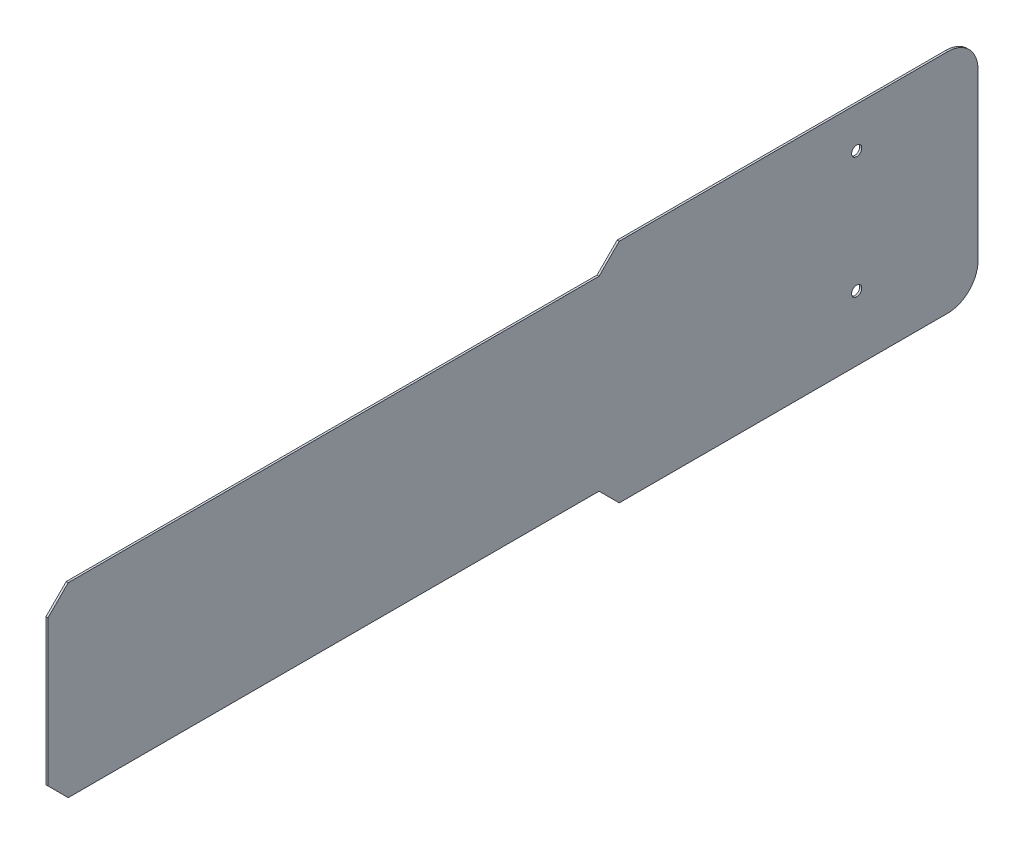
SolidWorks part; units mm, degrees
ref_plane "Front Plane" through (0, 0, 0) normal (0, 0, 1) x (1, 0, 0)
ref_plane "Top Plane" through (0, 0, 0) normal (0, 1, 0) x (1, 0, 0)
ref_plane "Right Plane" through (0, 0, 0) normal (1, 0, 0) x (0, 0, -1)
sketch "Sketch2" plane through (0, 0, 0) normal (-1, 0, 0) x (0, 1, 0)
  line L1 (-55.0231, 28.6615) -> (-32.6031, 28.6615)
  line L2 (-55.0231, 28.6615) -> (-55.0231, -63.3385)
  line L3 (-55.0231, -63.3385) -> (-32.6031, -63.3385)
  line L4 (-32.6031, 28.6615) -> (-32.6031, -63.3385)
  dimension "D1" = 92
  dimension "D2" = 22.42
extrude "Boss-Extrude2" add sketch "Sketch2" along normal blind 0.2 contours L2 L3 L4 L1
fillet "Fillet4" radius 3 1 edges at (-0.1, -55.0231, -28.6615)
fillet "Fillet7" radius 3 1 edges at (-0.1, -32.6031, -28.6615)
sketch "Sketch4" plane through (-0.2, 0, 0) normal (-1, 0, 0) x (0, 1, 0)
  line L0 (-55.0231, 25.6615) -> (-55.0231, -63.3385) construction
  line L1 (-55.0231, -8.8285) -> (-53.0231, -8.8285)
  line L2 (-55.0231, -8.8285) -> (-55.0231, -63.3385)
  line L3 (-55.0231, -63.3385) -> (-53.0231, -63.3385)
  line L4 (-53.0231, -8.8285) -> (-53.0231, -63.3385)
  line L5 (-55.0231, -63.3385) -> (-32.6031, -63.3385) construction
  dimension "D1" = 2
  dimension "D2" = 54.51
extrude "Cut-Extrude1" cut sketch "Sketch4" against normal blind 0.2
sketch "Sketch5" plane through (-0.2, 0, 0) normal (-1, 0, 0) x (0, 1, 0)
  line L1 (-34.6031, -8.8285) -> (-32.6031, -8.8285)
  line L2 (-34.6031, -8.8285) -> (-34.6031, -63.3385)
  line L3 (-34.6031, -63.3385) -> (-32.6031, -63.3385)
  line L4 (-32.6031, -8.8285) -> (-32.6031, -63.3385)
  dimension "D1" = 2
  dimension "D2" = 54.51
extrude "Cut-Extrude2" cut sketch "Sketch5" against normal blind 0.2
sketch "Sketch6" plane through (-0.2, 0, 0) normal (-1, 0, 0) x (0, 1, 0)
  line L0 (-53.0231, -63.3385) -> (-53.0231, -61.3385)
  line L1 (-53.0231, -63.3385) -> (-53.0231, -8.8285) construction
  line L2 (-53.0231, -63.3385) -> (-51.0231, -63.3385)
  line L3 (-53.0231, -63.3385) -> (-34.6031, -63.3385) construction
  line L4 (-53.0231, -61.3385) -> (-51.0231, -63.3385)
extrude "Cut-Extrude3" cut sketch "Sketch6" against normal blind 0.2
sketch "Sketch7" plane through (-0.2, 0, 0) normal (-1, 0, 0) x (0, 1, 0)
  line L0 (-34.6031, -63.3385) -> (-34.6031, -61.3385)
  line L1 (-34.6031, -8.8285) -> (-34.6031, -63.3385) construction
  line L2 (-34.6031, -63.3385) -> (-36.6031, -63.3385)
  line L3 (-51.0231, -63.3385) -> (-34.6031, -63.3385) construction
  line L4 (-34.6031, -61.3385) -> (-36.6031, -63.3385)
extrude "Cut-Extrude4" cut sketch "Sketch7" against normal blind 0.2
sketch "Sketch8" plane through (-0.2, 0, 0) normal (-1, 0, 0) x (0, 1, 0)
  line L0 (-53.0231, -8.8285) -> (-55.0231, -8.8285)
  line L2 (-55.0231, -8.8285) -> (-55.0231, -6.8285)
  line L3 (-55.0231, 25.6615) -> (-55.0231, -8.8285) construction
  line L4 (-55.0231, -6.8285) -> (-53.0231, -8.8285)
extrude "Cut-Extrude7" cut sketch "Sketch8" against normal blind 0.2
sketch "Sketch9" plane through (-0.2, 0, 0) normal (-1, 0, 0) x (0, 1, 0)
  line L0 (-34.6031, -8.8285) -> (-32.6031, -8.8285)
  line L1 (-32.6031, -8.8285) -> (-34.6031, -8.8285) construction
  line L2 (-32.6031, -8.8285) -> (-32.6031, -6.8285)
  line L3 (-32.6031, 25.6615) -> (-32.6031, -8.8285) construction
  line L4 (-32.6031, -6.8285) -> (-34.6031, -8.8285)
extrude "Cut-Extrude8" cut sketch "Sketch9" against normal blind 0.2
sketch "Sketch13" plane through (-0.2, 0, 0) normal (-1, 0, 0) x (0, 1, 0)
  circle A0 centre (-48.6031, 16.6615) radius 0.5
extrude "Cut-Extrude12" cut sketch "Sketch13" against normal blind 10
sketch "Sketch15" plane through (-0.2, 0, 0) normal (-1, 0, 0) x (0, 1, 0)
  circle A0 centre (-36.6031, 16.6615) radius 0.5
extrude "Cut-Extrude13" cut sketch "Sketch15" against normal blind 0.2
